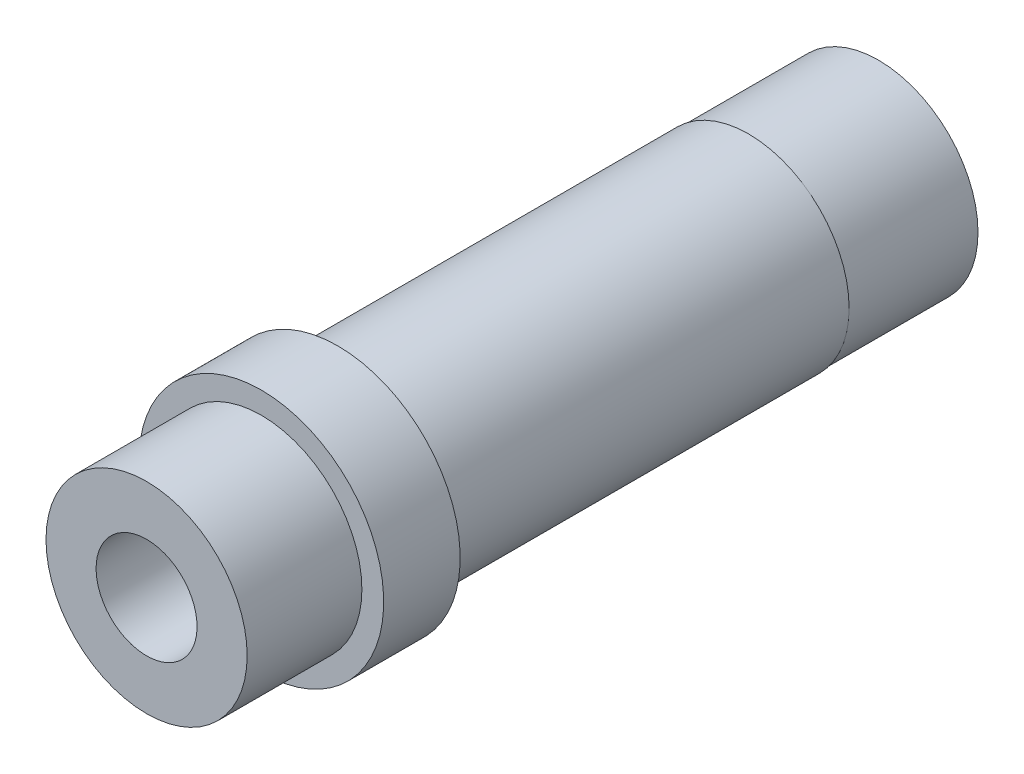
SolidWorks part; units mm, degrees
material "AISI 4340 Steel, normalized"
ref_plane "Front Plane" through (0, 0, 0) normal (0, 0, 1) x (1, 0, 0)
ref_plane "Top Plane" through (0, 0, 0) normal (0, 1, 0) x (1, 0, 0)
ref_plane "Right Plane" through (0, 0, 0) normal (1, 0, 0) x (0, 0, -1)
sketch "Sketch1" plane through (0, 0, 0) normal (1, 0, 0) x (0, 0, -1)
  line L0 (0, 0) -> (0, 160) construction
  line L1 (0, 160) -> (100, 160)
  line L2 (100, 160) -> (100, 131.5)
  line L4 (807, 130) -> (807, 0)
  line L7 (807, 0) -> (0, 0) construction
  line L8 (0, 0) -> (807, 0) construction
  line L12 (0, 0) -> (807, 0) construction
  line L13 (0, 0) -> (807, 0) construction
  line L17 (100, 131.5) -> (637, 131.5)
  line L18 (637, 131.5) -> (637, 130)
  line L19 (637, 130) -> (807, 130)
  line L20 (0, 0) -> (807, 0) construction
  line L21 (0, 160) -> (0, 131.5)
  line L22 (0, 131.5) -> (-50, 131.5)
  line L24 (-100, 131.5) -> (-150, 131.5)
  line L25 (-150, 131.5) -> (-150, 0)
  line L26 (-150, 0) -> (0, 0) construction
  line L27 (-150, 0) -> (807, 0)
  line L28 (-100, 131.5) -> (-50, 131.5)
  dimension "D1" = 263
  dimension "D2" = 100
  dimension "D3" = 50
  dimension "D4" = 320
  dimension "D5" = 50
  dimension "D6" = 260
  dimension "D7" = 263
  dimension "D8" = 170
  dimension "D9" = 807
  dimension "D10" = 100
  dimension "D11" = 263
revolve "Revolve1" add sketch "Sketch1" angle 360 about L27
sketch "Sketch2" plane through (0, 0, -807) normal (0, 0, -1) x (-1, 0, 0)
  circle A0 centre (0, 0) radius 66
  dimension "D1" = 132
extrude "Cut-Extrude1" cut sketch "Sketch2" against normal through all
